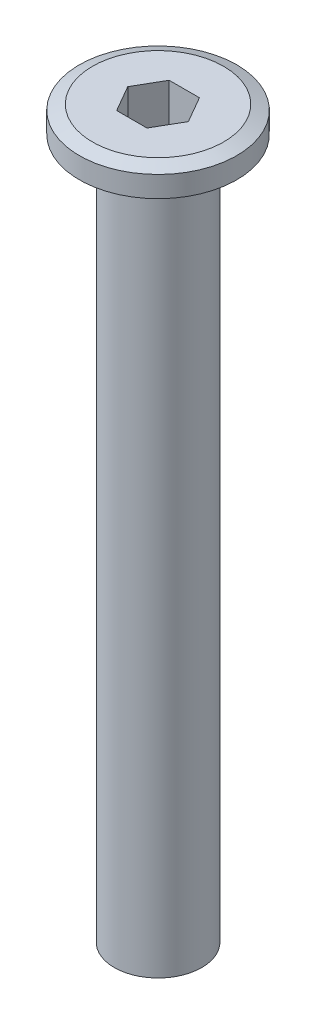
SolidWorks part; units mm, degrees
ref_plane "Front Plane" through (0, 0, 0) normal (0, 0, 1) x (1, 0, 0)
ref_plane "Top Plane" through (0, 0, 0) normal (0, 1, 0) x (1, 0, 0)
ref_plane "Right Plane" through (0, 0, 0) normal (1, 0, 0) x (0, 0, -1)
sketch "Sketch1" plane through (0, 0, 0) normal (0, 0, 1) x (1, 0, 0)
  line L0 (0, 0) -> (0, 1.5)
  line L1 (-2.5, 0) -> (2.5, 0)
  line L5 (-4.5, 0) -> (4.5, 0)
  line L6 (-4.5, 0) -> (-4.5, 1.5)
  line L7 (-4.5, 1.5) -> (4.5, 1.5)
  line L8 (4.5, 0) -> (4.5, 1.5)
  line L9 (-4.5, 1.2) -> (-3.75, 1.5)
  point P1 (0, 0)
  point P8 (0, 1.5)
  dimension "D1" = 3.75
  dimension "D3" = 9
  dimension "D4" = 1.5
  dimension "D6" = 1.2
revolve "Revolve1" add sketch "Sketch1" angle 360 about L0
sketch "Sketch2" plane through (0, 1.5, 0) normal (0, 1, 0) x (1, 0, 0)
  line L1 (1.7321, 0) -> (0.866, 1.5)
  line L2 (0.866, 1.5) -> (-0.866, 1.5)
  line L3 (-0.866, 1.5) -> (-1.7321, 0)
  line L4 (-1.7321, 0) -> (-0.866, -1.5)
  line L5 (-0.866, -1.5) -> (0.866, -1.5)
  line L6 (0.866, -1.5) -> (1.7321, 0)
  circle A0 centre (0, 0) radius 1.5 construction
  dimension "D1" = 3
sketch "Sketch3" plane through (0, 0, 0) normal (0, -1, 0) x (1, 0, 0)
  circle A0 centre (0, 0) radius 2.5
  dimension "D1" = 5
extrude "Boss-Extrude1" add sketch "Sketch3" along normal blind 40
extrude "Cut-Extrude2" cut sketch "Sketch2" against normal blind 3 contours L1 L2 L3 L4 L5 L6
